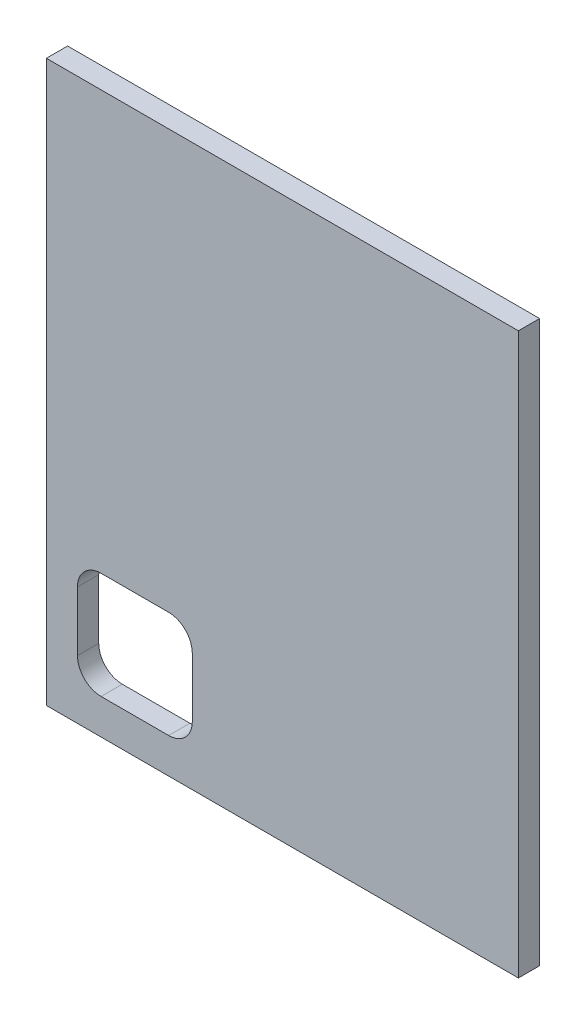
SolidWorks part; units mm, degrees
ref_plane "Front Plane" through (0, 0, 0) normal (0, 0, 1) x (1, 0, 0)
ref_plane "Top Plane" through (0, 0, 0) normal (0, 1, 0) x (1, 0, 0)
ref_plane "Right Plane" through (0, 0, 0) normal (1, 0, 0) x (0, 0, -1)
sketch "Sketch1" plane through (0, 0, 0) normal (0, 0, 1) x (1, 0, 0)
  line L1 (0, 0) -> (50.8, 0)
  line L2 (0, 0) -> (0, 60.325)
  line L3 (0, 60.325) -> (50.8, 60.325)
  line L4 (50.8, 0) -> (50.8, 60.325)
  line L5 (5.8869, 15.2648) -> (13.1631, 15.2648)
  line L6 (3.3469, 12.7248) -> (3.3469, 6.3252)
  line L7 (5.8869, 3.7852) -> (13.1631, 3.7852)
  line L8 (15.7031, 12.7248) -> (15.7031, 6.3252)
  arc A1 (13.1631, 15.2648) -> (15.7031, 12.7248) centre (13.1631, 12.7248) cw
  arc A2 (3.3469, 12.7248) -> (5.8869, 15.2648) centre (5.8869, 12.7248) cw
  arc A3 (5.8869, 3.7852) -> (3.3469, 6.3252) centre (5.8869, 6.3252) cw
  arc A4 (15.7031, 6.3252) -> (13.1631, 3.7852) centre (13.1631, 6.3252) cw
extrude "Extrude2" add sketch "Sketch1" against normal blind 2.286
